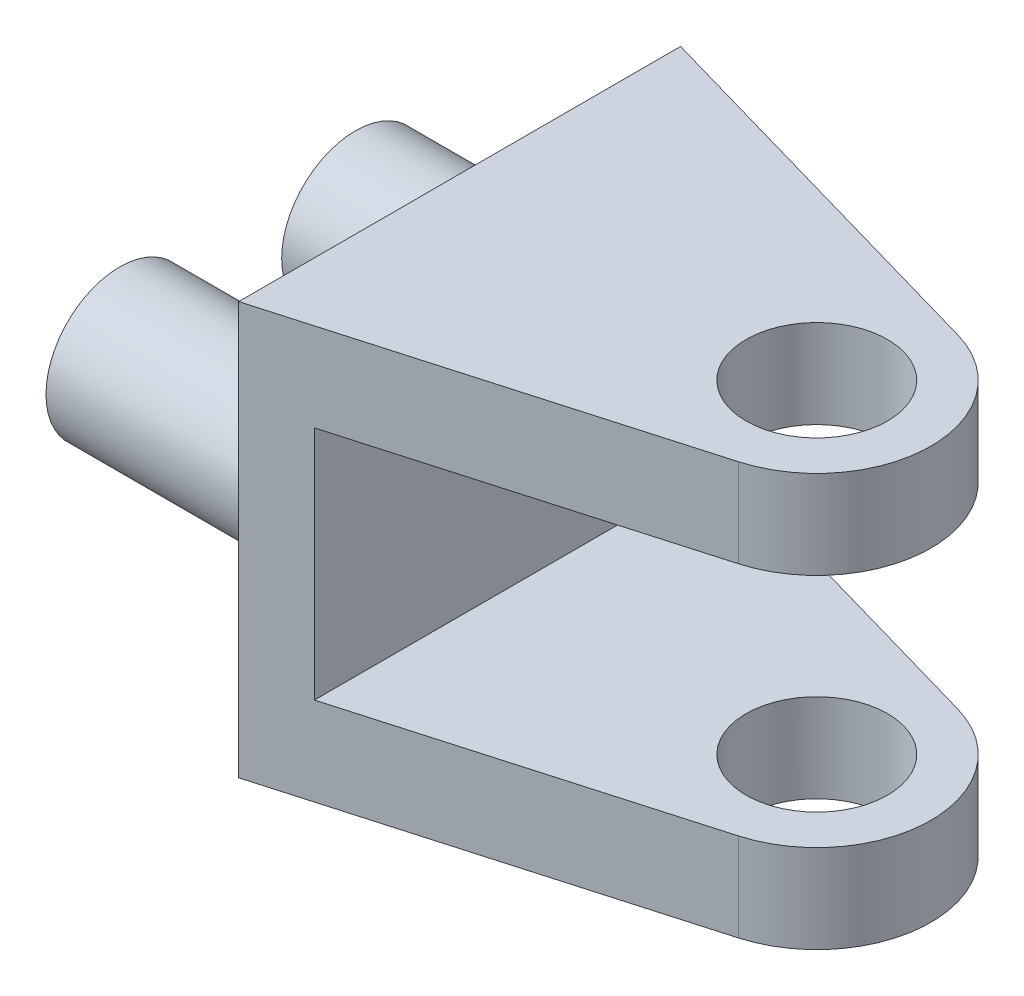
SolidWorks part; units mm, degrees
ref_plane "Front Plane" through (0, 0, 0) normal (0, 0, 1) x (1, 0, 0)
ref_plane "Top Plane" through (0, 0, 0) normal (0, 1, 0) x (1, 0, 0)
ref_plane "Right Plane" through (0, 0, 0) normal (1, 0, 0) x (0, 0, -1)
sketch "Sketch1" plane through (0, 0, 0) normal (0, 1, 0) x (1, 0, 0)
  line L0 (0, 0) -> (-12.125, 0) construction
  line L1 (-12.125, 7.5) -> (-12.125, -7.5)
  line L2 (-12.125, 7.5) -> (1.066, 3.7255)
  line L3 (-12.125, -7.5) -> (1.066, -3.7255)
  line L4 (-12.125, 0) -> (3.875, 0) construction
  arc A0 (1.066, -3.7255) -> (1.066, 3.7255) centre (0, 0) ccw
  circle A1 centre (0, 0) radius 2.4
  point P4 (0, 0)
  point P8 (-12.125, 0)
  dimension "D1" = 7.75
  dimension "D4" = 4.8
  dimension "D2" = 15
  dimension "D3" = 16
extrude "Boss-Extrude1" add sketch "Sketch1" along normal blind 14
sketch "Sketch3" plane through (0, 0, 0) normal (0, 0, 1) x (1, 0, 0)
  line L0 (-12.125, 14) -> (1.066, 14) construction
  line L1 (-10.125, 11) -> (6.6522, 11)
  line L2 (-10.125, 11) -> (-10.125, 3)
  line L3 (-10.125, 3) -> (6.6522, 3)
  line L4 (6.6522, 11) -> (6.6522, 3)
  line L5 (-12.125, 0) -> (1.066, 0) construction
  line L6 (-12.125, 14) -> (-12.125, 0) construction
  dimension "D1" = 3
  dimension "D2" = 3
  dimension "D3" = 2
extrude "Cut-Extrude2" cut sketch "Sketch3" against normal mid plane 52
sketch "Sketch4" plane through (-12.125, 0, 0) normal (-1, 0, 0) x (0, 0, 1)
  line L0 (0, 14) -> (0, 0) construction
  line L1 (-7.5, 14) -> (7.5, 14) construction
  line L6 (-4, 7) -> (4, 7) construction
  circle A0 centre (-4, 7) radius 1.5
  circle A1 centre (4, 7) radius 1.5
  circle A2 centre (4, 7) radius 2.5
  circle A3 centre (-4, 7) radius 2.5
  dimension "D1" = 5
  dimension "D2" = 3
  dimension "D3" = 8
  dimension "D4" = 4
  dimension "D5" = 7
extrude "Boss-Extrude2" add sketch "Sketch4" along normal blind 7.54
